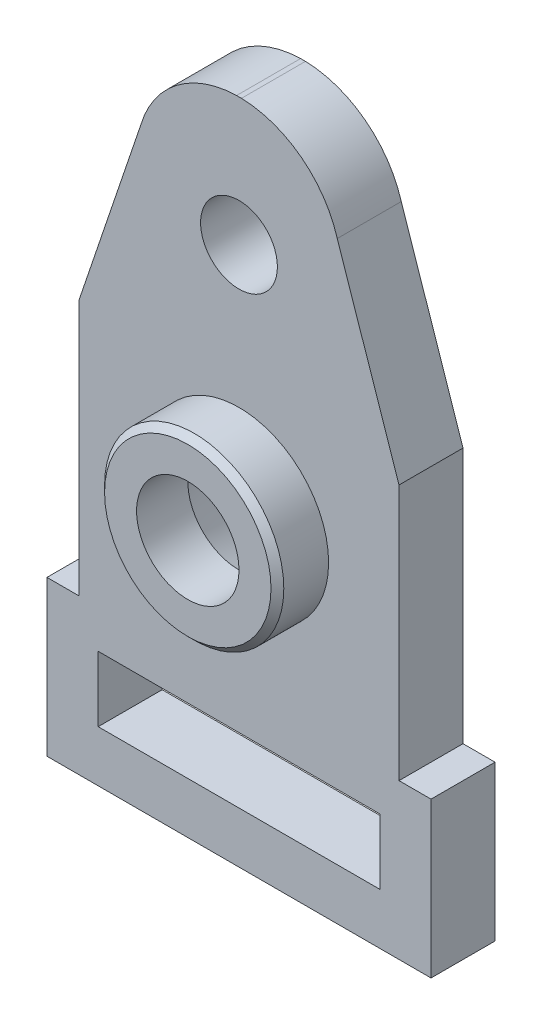
SolidWorks part; units mm, degrees
ref_plane "Спереди" through (0, 0, 0) normal (0, 0, 1) x (1, 0, 0)
ref_plane "Сверху" through (0, 0, 0) normal (0, 1, 0) x (1, 0, 0)
ref_plane "Справа" through (0, 0, 0) normal (1, 0, 0) x (0, 0, -1)
sketch "Эскиз1" plane through (0, 0, 0) normal (0, 0, 1) x (1, 0, 0)
  line L0 (-12.5, 0) -> (12.5, 0) construction
  line L1 (0.1908, 20) -> (-0.1908, 20)
  line L2 (12.5, 0) -> (12.5, -20)
  line L3 (12.5, -20) -> (-12.5, -20)
  line L4 (-12.5, 0) -> (-12.5, -20)
  line L5 (12.5, 20) -> (-12.5, -20) construction
  line L6 (12.5, -20) -> (-12.5, 20) construction
  line L7 (-12.5, 0) -> (-7.6749, 14.2598)
  line L8 (0, 20) -> (0, 0) construction
  line L9 (12.5, 0) -> (7.6749, 14.2598)
  line L10 (-15, -23) -> (15, -23)
  line L11 (15, -20) -> (-15, -20)
  line L12 (15, -20) -> (15, -32.1)
  line L13 (15, -32.1) -> (-15, -32.1)
  line L14 (-15, -20) -> (-15, -32.1)
  line L15 (15, -20) -> (-15, -32.1) construction
  line L16 (15, -32.1) -> (-15, -20) construction
  line L17 (-15, -28.1) -> (15, -28.1)
  line L18 (-11, -23) -> (-11, -28.1)
  line L19 (11, -23) -> (11, -28.1)
  arc A0 (7.6749, 14.2598) -> (-7.6749, 14.2598) centre (0, 12.0023) ccw
  point P0 (0, 0)
  point P11 (0, -26.05)
  dimension "D3" = 16
  dimension "D1" = 40
  dimension "D2" = 25
  dimension "D4" = 30
  dimension "D5" = 0
  dimension "D6" = 3
  dimension "D7" = 4
  dimension "D8" = 5.1
  dimension "D9" = 4
extrude "Бобышка-Вытянуть1" add sketch "Эскиз1" along normal blind 5 contours L9 A0 L1 L7 L4 L3 L2 | L17 L14 L13 L12 | L10 L19 L17 L12 | L11 L14 L10 L12 L3 | L18 L10 L14 L17
sketch "Эскиз2" plane through (0, 0, 5) normal (0, 0, 1) x (1, 0, 0)
  line L0 (0, -23) -> (0, -8) construction
  line L1 (-11, -23) -> (11, -23) construction
  line L2 (0, -8) -> (0, 10) construction
  circle A0 centre (0, 10) radius 3
  circle A1 centre (0, -8) radius 4 construction
  dimension "D1" = 6
  dimension "D2" = 8
  dimension "D3" = 10
  dimension "D4" = 28
extrude "Вырез-Вытянуть1" cut sketch "Эскиз2" against normal blind 10
sketch "Эскиз3" plane through (0, 0, 5) normal (0, 0, 1) x (1, 0, 0)
  line L0 (0, 0) -> (0, -8) construction
  circle A0 centre (0, -8) radius 7
  circle A1 centre (0, -8) radius 4
  dimension "D1" = 14
  dimension "D2" = 8
  dimension "D3" = 8
extrude "Бобышка-Вытянуть2" add sketch "Эскиз3" along normal blind 4
chamfer "Фаска1" distance 0.5 angle 45 1 edges at (7, -8, 9)
sketch "Эскиз4" plane through (0, 0, 5) normal (0, 0, 1) x (1, 0, 0)
  circle A0 centre (0, -8) radius 4
extrude "Вырез-Вытянуть2" cut sketch "Эскиз4" against normal blind 10 draft 20 draft outward yes
